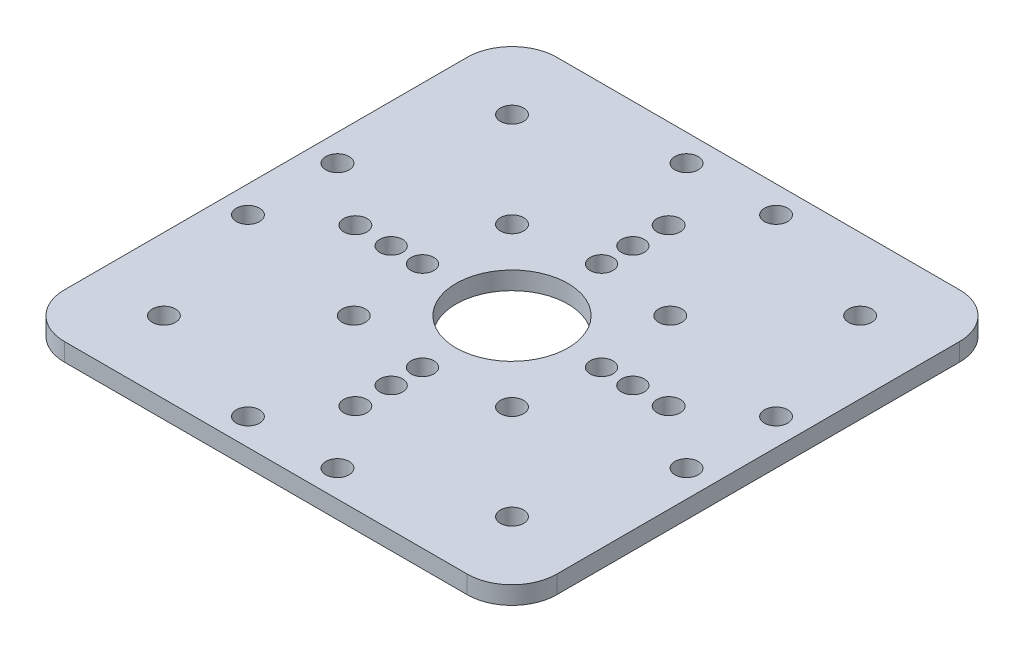
SolidWorks part; units mm, degrees
ref_plane "前视基准面" through (0, 0, 0) normal (0, 0, 1) x (1, 0, 0)
ref_plane "上视基准面" through (0, 0, 0) normal (0, 1, 0) x (1, 0, 0)
ref_plane "右视基准面" through (0, 0, 0) normal (1, 0, 0) x (0, 0, -1)
other "Configuration Table"
sketch "草图1" plane through (0, 0, 0) normal (0, 1, 0) x (1, 0, 0)
  line L1 (55, 55) -> (-55, 55)
  line L2 (-55, 55) -> (-55, -55)
  line L3 (-55, -55) -> (55, -55)
  line L4 (55, -55) -> (55, 55)
  circle A0 centre (0, 0) radius 55 construction
  dimension "D1" = 110
extrude "凸台-拉伸1" add sketch "草图1" along normal blind 4
sketch "草图2" plane through (0, 0, 0) normal (0, 1, 0) x (1, 0, 0)
  line L0 (0, 0) -> (0, 35) construction
  line L1 (0, 0) -> (-35, 0) construction
  circle A0 centre (0, 0) radius 35 construction
  circle A1 centre (0, 35) radius 2.6
  circle A2 centre (35, 0) radius 2.6
  circle A3 centre (0, -35) radius 2.6
  circle A4 centre (-35, 0) radius 2.6
  point P15 (0, 0)
  dimension "D1" = 70
  dimension "D2" = 5.2
  dimension "D3" = 90
  dimension "D4" = 4
extrude "切除-拉伸1" cut sketch "草图2" along normal through all
sketch "草图3" plane through (0, 4, 0) normal (0, 1, 0) x (1, 0, 0)
  circle A0 centre (0, 0) radius 27 construction
  circle A1 centre (0, 27) radius 2.55
  circle A2 centre (27, 0) radius 2.55
  circle A3 centre (0, -27) radius 2.55
  circle A4 centre (-27, 0) radius 2.55
  point P14 (0, 0)
  dimension "D1" = 54
  dimension "D2" = 5.1
  dimension "D3" = 4
extrude "切除-拉伸2" cut sketch "草图3" against normal through all
sketch "草图4" plane through (0, 4, 0) normal (0, 1, 0) x (1, 0, 0)
  line L0 (0, 0) -> (0, 55) construction
  line L1 (55, 55) -> (-55, 55) construction
  line L2 (-10, 49) -> (10, 49) construction
  line L3 (49, 10) -> (49, -10) construction
  line L4 (10, -49) -> (-10, -49) construction
  line L5 (-49, -10) -> (-49, 10) construction
  circle A0 centre (-10, 49) radius 2.6
  circle A1 centre (10, 49) radius 2.6
  circle A2 centre (49, 10) radius 2.6
  circle A3 centre (49, -10) radius 2.6
  circle A4 centre (10, -49) radius 2.6
  circle A5 centre (-10, -49) radius 2.6
  circle A6 centre (-49, -10) radius 2.6
  circle A7 centre (-49, 10) radius 2.6
  point P24 (0, 0)
  dimension "D2" = 5.2
  dimension "D1" = 20
  dimension "D3" = 49
  dimension "D4" = 4
extrude "切除-拉伸3" cut sketch "草图4" against normal through all
sketch "草图6" plane through (0, 4, 0) normal (0, 1, 0) x (1, 0, 0)
  line L0 (0, 0) -> (-55, 0) construction
  line L1 (0, 0) -> (-38.8909, 38.8909) construction
  circle A0 centre (0, 0) radius 55 construction
  circle A1 centre (-38.8909, 38.8909) radius 2.6
  circle A2 centre (38.8909, 38.8909) radius 2.6
  circle A3 centre (38.8909, -38.8909) radius 2.6
  circle A4 centre (-38.8909, -38.8909) radius 2.6
  point P15 (0, 0)
  dimension "D1" = 110
  dimension "D3" = 5.2
  dimension "D2" = 45
  dimension "D4" = 4
extrude "切除-拉伸4" cut sketch "草图6" against normal blind 10
sketch "草图7" plane through (0, 4, 0) normal (0, 1, 0) x (1, 0, 0)
  line L0 (0, 0) -> (-25, 0) construction
  line L1 (-17.6777, 17.6777) -> (0, 0) construction
  circle A0 centre (0, 0) radius 25 construction
  circle A1 centre (-17.6777, 17.6777) radius 2.6
  circle A2 centre (17.6777, 17.6777) radius 2.6
  circle A3 centre (17.6777, -17.6777) radius 2.6
  circle A4 centre (-17.6777, -17.6777) radius 2.6
  point P15 (0, 0)
  dimension "D1" = 50
  dimension "D3" = 5.2
  dimension "D2" = 45
  dimension "D4" = 4
extrude "切除-拉伸5" cut sketch "草图7" against normal through all
sketch "草图8" plane through (0, 4, 0) normal (0, 1, 0) x (1, 0, 0)
  circle A0 centre (0, 0) radius 20 construction
  circle A1 centre (0, 20) radius 2.55
  circle A2 centre (20, 0) radius 2.55
  circle A3 centre (0, -20) radius 2.55
  circle A4 centre (-20, 0) radius 2.55
  point P14 (0, 0)
  dimension "D1" = 40
  dimension "D2" = 5.1
  dimension "D3" = 4
extrude "切除-拉伸6" cut sketch "草图8" against normal through all
sketch "草图9" plane through (0, 4, 0) normal (0, 1, 0) x (1, 0, 0)
  circle A0 centre (0, 0) radius 12.5
  dimension "D1" = 25
extrude "切除-拉伸7" cut sketch "草图9" against normal through all
fillet "圆角1" radius 10 4 edges at (-55, 2, -55) (55, 2, -55) (55, 2, 55) (-55, 2, 55)
